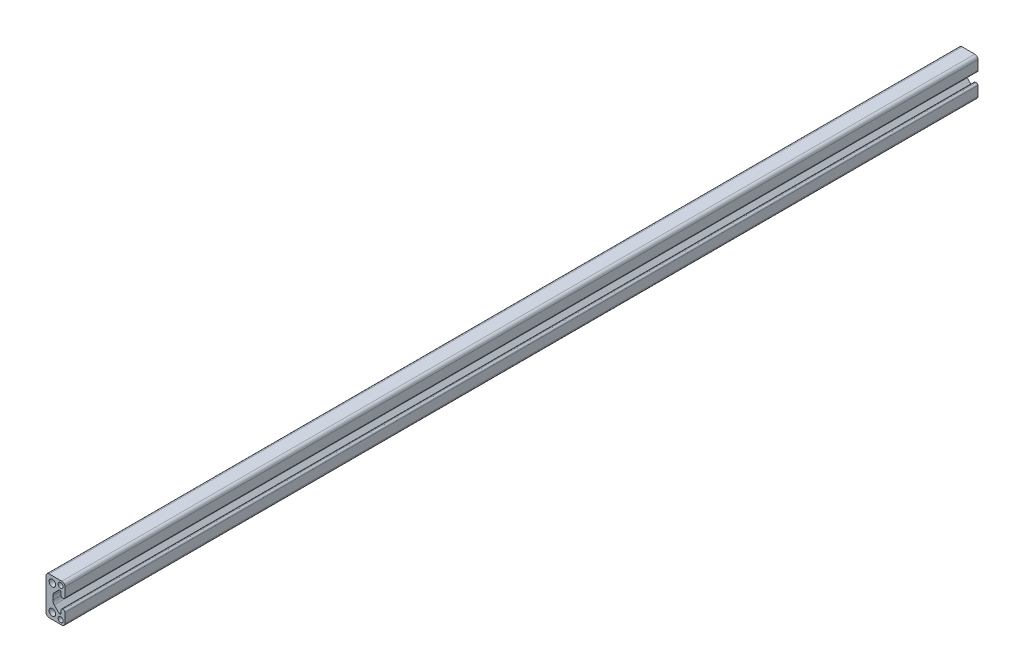
SolidWorks part; units mm, degrees
ref_plane "Front Plane" through (0, 0, 0) normal (0, 0, 1) x (1, 0, 0)
ref_plane "Top Plane" through (0, 0, 0) normal (0, 1, 0) x (1, 0, 0)
ref_plane "Right Plane" through (0, 0, 0) normal (1, 0, 0) x (0, 0, -1)
sketch "Sketch1" plane through (0, 0, 0) normal (0, 0, 1) x (1, 0, 0)
  line L0 (-6.35, 0) -> (6.35, 0) construction
  line L1 (6.35, 4.3011) -> (6.35, 10.5833)
  line L2 (4.2333, 12.7) -> (-4.2333, 12.7)
  line L3 (-6.35, 10.5833) -> (-6.35, 0)
  line L4 (-1.778, 0) -> (-1.778, 1.27)
  line L5 (-0.8467, 3.5339) -> (2.4133, 6.7939)
  line L6 (2.7725, 6.9427) -> (3.048, 6.9427)
  line L7 (3.6407, 6.35) -> (3.6407, 4.3011)
  line L8 (4.6905, 3.2512) -> (5.3001, 3.2512)
  circle A2 centre (3.429, 9.906) radius 1.6933
  circle A3 centre (-2.1167, 8.4667) radius 2.2013
  arc A4 (6.35, 10.5833) -> (4.2333, 12.7) centre (4.2333, 10.5833) ccw
  arc A5 (-4.2333, 12.7) -> (-6.35, 10.5833) centre (-4.2333, 10.5833) ccw
  arc A6 (-0.8467, 3.5339) -> (-1.778, 1.27) centre (1.4393, 1.27) ccw
  arc A7 (2.7725, 6.9427) -> (2.4133, 6.7939) centre (2.7725, 6.4347) ccw
  arc A8 (3.6407, 6.35) -> (3.048, 6.9427) centre (3.048, 6.35) ccw
  arc A9 (3.6407, 4.3011) -> (4.6905, 3.2512) centre (4.6905, 4.3011) ccw
  arc A10 (5.3001, 3.2512) -> (6.35, 4.3011) centre (5.3001, 4.3011) ccw
  dimension "D8" = 2.1167
  dimension "D9" = 3.3867
  dimension "D10" = 4.4027
  dimension "D13" = 1.0499
  dimension "D14" = 3.2173
  dimension "D16" = 0.508
  dimension "D17" = 0.5927
  dimension "Rail Height" = 25.4
  dimension "Rail Width" = 12.7
  dimension "D1" = 4.572
  dimension "D2" = 135
  dimension "D3" = 1.27
  dimension "D4" = 16.9333
  dimension "D5" = 4.2333
  dimension "D7" = 2.921
  dimension "D6" = 19.812
  dimension "TSlot Wdith" = 6.5024
  dimension "D11" = 2.7093
  dimension "D12" = 6.9427
  dimension "D15" = 5.5033
sketch "Sketch2" plane through (0, 0, 0) normal (1, 0, 0) x (0, 0, -1)
  line L0 (-914.4, 0) -> (914.4, 0)
  point P2 (-876.3, 0)
  point P3 (876.3, 0)
  dimension "Length" = 1828.8
  dimension "D1" = 38.1
  dimension "D2" = 38.1
sketch "Sketch3" plane through (0, 0, 0) normal (0, 0, 1) x (1, 0, 0)
  line L0 (-1.778, 0) -> (-1.778, 1.27) construction
  line L1 (-0.8467, 3.5339) -> (2.4133, 6.7939) construction
  line L2 (2.7725, 6.9427) -> (3.048, 6.9427) construction
  line L3 (3.6407, 6.35) -> (3.6407, 4.3011) construction
  line L4 (4.6905, 3.2512) -> (5.3001, 3.2512) construction
  line L5 (6.35, 4.3011) -> (6.35, 10.5833) construction
  line L6 (4.2333, 12.7) -> (-4.2333, 12.7) construction
  line L7 (-6.35, 10.5833) -> (-6.35, 0) construction
  line L8 (-1.778, 0) -> (-1.778, 1.27)
  line L9 (-0.8467, 3.5339) -> (2.4133, 6.7939)
  line L10 (2.7725, 6.9427) -> (3.048, 6.9427)
  line L11 (3.6407, 6.35) -> (3.6407, 4.3011)
  line L12 (4.6905, 3.2512) -> (5.3001, 3.2512)
  line L13 (6.35, 4.3011) -> (6.35, 10.5833)
  line L14 (4.2333, 12.7) -> (-4.2333, 12.7)
  line L15 (-6.35, 10.5833) -> (-6.35, 0)
  line L16 (-6.35, 0) -> (-1.778, 0)
  arc A0 (-0.8467, 3.5339) -> (-1.778, 1.27) centre (1.4393, 1.27) ccw construction
  circle A1 centre (-2.1167, 8.4667) radius 2.2013
  circle A2 centre (-2.1167, 8.4667) radius 2.2013
  circle A3 centre (3.429, 9.906) radius 1.6933
  circle A4 centre (3.429, 9.906) radius 1.6933
  arc A5 (2.7725, 6.9427) -> (2.4133, 6.7939) centre (2.7725, 6.4347) ccw construction
  arc A6 (3.6407, 6.35) -> (3.048, 6.9427) centre (3.048, 6.35) ccw construction
  arc A7 (3.6407, 4.3011) -> (4.6905, 3.2512) centre (4.6905, 4.3011) ccw construction
  arc A8 (5.3001, 3.2512) -> (6.35, 4.3011) centre (5.3001, 4.3011) ccw construction
  arc A9 (6.35, 10.5833) -> (4.2333, 12.7) centre (4.2333, 10.5833) ccw construction
  arc A10 (-4.2333, 12.7) -> (-6.35, 10.5833) centre (-4.2333, 10.5833) ccw construction
  arc A11 (-0.8467, 3.5339) -> (-1.778, 1.27) centre (1.4393, 1.27) ccw
  arc A12 (2.7725, 6.9427) -> (2.4133, 6.7939) centre (2.7725, 6.4347) ccw
  arc A13 (3.6407, 6.35) -> (3.048, 6.9427) centre (3.048, 6.35) ccw
  arc A14 (3.6407, 4.3011) -> (4.6905, 3.2512) centre (4.6905, 4.3011) ccw
  arc A15 (5.3001, 3.2512) -> (6.35, 4.3011) centre (5.3001, 4.3011) ccw
  arc A16 (6.35, 10.5833) -> (4.2333, 12.7) centre (4.2333, 10.5833) ccw
  arc A17 (-4.2333, 12.7) -> (-6.35, 10.5833) centre (-4.2333, 10.5833) ccw
  dimension "D1" = 0
  dimension "D2" = 0
extrude "Boss-Extrude1" add sketch "Sketch3" along normal mid plane 1828.8
mirror "Mirror1" about plane through (0, 0, 0) normal (0, 1, 0) of bodies 104
sketch "Sketch4" plane through (0, 0, -914.4) normal (0, 0, -1) x (-1, 0, 0)
  line L14 (1.778, 1.27) -> (1.778, -1.27)
  line L15 (0.8467, -3.5339) -> (-2.4133, -6.7939)
  line L16 (-2.7725, -6.9427) -> (-3.048, -6.9427)
  line L17 (-3.6407, -6.35) -> (-3.6407, -4.3011)
  line L18 (-4.6905, -3.2512) -> (-5.3001, -3.2512)
  line L19 (-6.35, -4.3011) -> (-6.35, -10.5833)
  line L20 (-4.2333, -12.7) -> (4.2333, -12.7)
  line L21 (6.35, -10.5833) -> (6.35, 10.5833)
  line L22 (4.2333, 12.7) -> (-4.2333, 12.7)
  line L23 (-6.35, 10.5833) -> (-6.35, 4.3011)
  line L24 (-5.3001, 3.2512) -> (-4.6905, 3.2512)
  line L25 (-3.6407, 4.3011) -> (-3.6407, 6.35)
  line L26 (-3.048, 6.9427) -> (-2.7725, 6.9427)
  line L27 (-2.4133, 6.7939) -> (0.8467, 3.5339)
  line L28 (1.778, 1.27) -> (1.778, -1.27)
  line L29 (0.8467, -3.5339) -> (-2.4133, -6.7939)
  line L30 (-2.7725, -6.9427) -> (-3.048, -6.9427)
  line L31 (-3.6407, -6.35) -> (-3.6407, -4.3011)
  line L32 (-4.6905, -3.2512) -> (-5.3001, -3.2512)
  line L33 (-6.35, -4.3011) -> (-6.35, -10.5833)
  line L34 (-4.2333, -12.7) -> (4.2333, -12.7)
  line L35 (6.35, -10.5833) -> (6.35, 10.5833)
  line L36 (4.2333, 12.7) -> (-4.2333, 12.7)
  line L37 (-6.35, 10.5833) -> (-6.35, 4.3011)
  line L38 (-5.3001, 3.2512) -> (-4.6905, 3.2512)
  line L39 (-3.6407, 4.3011) -> (-3.6407, 6.35)
  line L40 (-3.048, 6.9427) -> (-2.7725, 6.9427)
  line L41 (-2.4133, 6.7939) -> (0.8467, 3.5339)
  arc A14 (0.8467, -3.5339) -> (1.778, -1.27) centre (-1.4393, -1.27) ccw
  arc A15 (-2.7725, -6.9427) -> (-2.4133, -6.7939) centre (-2.7725, -6.4347) ccw
  arc A16 (-3.6407, -6.35) -> (-3.048, -6.9427) centre (-3.048, -6.35) ccw
  arc A17 (-3.6407, -4.3011) -> (-4.6905, -3.2512) centre (-4.6905, -4.3011) ccw
  arc A18 (-5.3001, -3.2512) -> (-6.35, -4.3011) centre (-5.3001, -4.3011) ccw
  arc A19 (-6.35, -10.5833) -> (-4.2333, -12.7) centre (-4.2333, -10.5833) ccw
  arc A20 (4.2333, -12.7) -> (6.35, -10.5833) centre (4.2333, -10.5833) ccw
  arc A21 (6.35, 10.5833) -> (4.2333, 12.7) centre (4.2333, 10.5833) ccw
  arc A22 (-4.2333, 12.7) -> (-6.35, 10.5833) centre (-4.2333, 10.5833) ccw
  arc A23 (-6.35, 4.3011) -> (-5.3001, 3.2512) centre (-5.3001, 4.3011) ccw
  arc A24 (-4.6905, 3.2512) -> (-3.6407, 4.3011) centre (-4.6905, 4.3011) ccw
  arc A25 (-3.048, 6.9427) -> (-3.6407, 6.35) centre (-3.048, 6.35) ccw
  arc A26 (-2.4133, 6.7939) -> (-2.7725, 6.9427) centre (-2.7725, 6.4347) ccw
  arc A27 (1.778, 1.27) -> (0.8467, 3.5339) centre (-1.4393, 1.27) ccw
  arc A28 (0.8467, -3.5339) -> (1.778, -1.27) centre (-1.4393, -1.27) ccw
  arc A29 (-2.7725, -6.9427) -> (-2.4133, -6.7939) centre (-2.7725, -6.4347) ccw
  arc A30 (-3.6407, -6.35) -> (-3.048, -6.9427) centre (-3.048, -6.35) ccw
  arc A31 (-3.6407, -4.3011) -> (-4.6905, -3.2512) centre (-4.6905, -4.3011) ccw
  arc A32 (-5.3001, -3.2512) -> (-6.35, -4.3011) centre (-5.3001, -4.3011) ccw
  arc A33 (-6.35, -10.5833) -> (-4.2333, -12.7) centre (-4.2333, -10.5833) ccw
  arc A34 (4.2333, -12.7) -> (6.35, -10.5833) centre (4.2333, -10.5833) ccw
  arc A35 (6.35, 10.5833) -> (4.2333, 12.7) centre (4.2333, 10.5833) ccw
  arc A36 (-4.2333, 12.7) -> (-6.35, 10.5833) centre (-4.2333, 10.5833) ccw
  arc A37 (-6.35, 4.3011) -> (-5.3001, 3.2512) centre (-5.3001, 4.3011) ccw
  arc A38 (-4.6905, 3.2512) -> (-3.6407, 4.3011) centre (-4.6905, 4.3011) ccw
  arc A39 (-3.048, 6.9427) -> (-3.6407, 6.35) centre (-3.048, 6.35) ccw
  arc A40 (-2.4133, 6.7939) -> (-2.7725, 6.9427) centre (-2.7725, 6.4347) ccw
  arc A41 (1.778, 1.27) -> (0.8467, 3.5339) centre (-1.4393, 1.27) ccw
  dimension "D1" = 0
extrude "Cut-Extrude1" cut sketch "Sketch4" against normal blind 1219.2
equation "\"D1@Sketch1\"=\"Rail Width@Sketch1\"*0.36"
equation "\"D3@Sketch1\"=\"Rail Height@Sketch1\"*0.05"
equation "\"D4@Sketch1\"=\"Rail Height@Sketch1\"*2/3"
equation "\"D5@Sketch1\"=\"D4@Sketch1\"*1/4"
equation "\"D7@Sketch1\"=\"Rail Width@Sketch1\"*0.23"
equation "\"D6@Sketch1\"=\"Rail Height@Sketch1\"*0.78"
equation "\"D8@Sketch1\"=\"D4@Sketch1\"*1/8"
equation "\"D9@Sketch1\"=\"D4@Sketch1\"*1/5"
equation "\"D10@Sketch1\"=\"D4@Sketch1\"*0.26"
equation "\"D11@Sketch1\"=\"D4@Sketch1\"*0.16"
equation "\"D12@Sketch1\"=\"D4@Sketch1\"*0.41"
equation "\"D13@Sketch1\"=\"D4@Sketch1\"*0.062"
equation "\"D14@Sketch1\"=\"D9@Sketch1\"*0.95"
equation "\"D15@Sketch1\"=\"D4@Sketch1\"*0.325"
equation "\"D16@Sketch1\"=\"D4@Sketch1\"*0.03"
equation "\"D17@Sketch1\"=\"D4@Sketch1\"*0.035"
equation "\"D2@Sketch2\"=\"D1@Sketch2\""
equation "\"D1@Boss-Extrude1\"=\"length@sketch2\""
